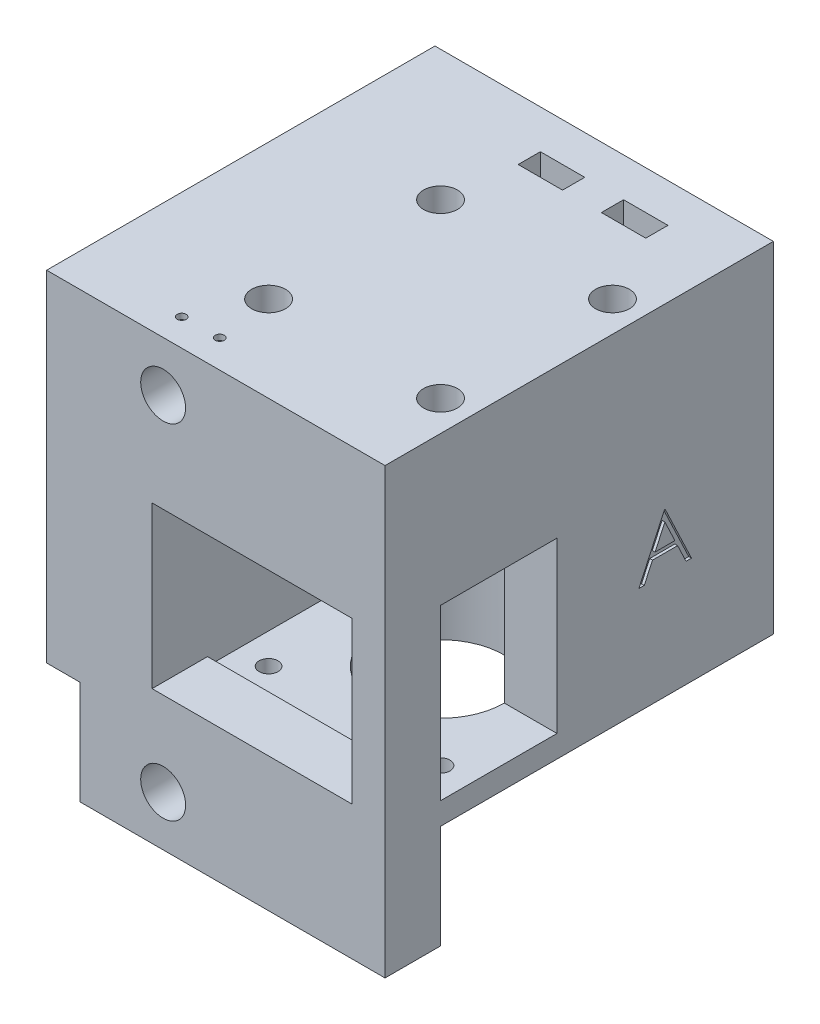
SolidWorks part; units mm, degrees
ref_plane "Front Plane" through (0, 0, 0) normal (0, 0, 1) x (1, 0, 0)
ref_plane "Top Plane" through (0, 0, 0) normal (0, 1, 0) x (1, 0, 0)
ref_plane "Right Plane" through (0, 0, 0) normal (1, 0, 0) x (0, 0, -1)
sketch "Sketch1" plane through (0, 0, 0) normal (0, 1, 0) x (1, 0, 0)
  line L0 (21, 42) -> (21, 33.028) construction
  line L1 (0, 0) -> (42, 0)
  line L2 (0, 0) -> (0, 42)
  line L3 (0, 42) -> (42, 42)
  line L4 (42, 0) -> (42, 42)
  line L5 (0, 21) -> (12.4001, 21) construction
  circle A0 centre (5.5, 36.5) radius 1.7
  circle A1 centre (36.5, 36.5) radius 1.7
  circle A2 centre (5.5, 5.5) radius 1.7
  circle A3 centre (36.5, 5.5) radius 1.7
  circle A4 centre (21, 21) radius 11.5
  dimension "D6" = 3.4
  dimension "D8" = 23
  dimension "D1" = 42
  dimension "D2" = 42
  dimension "D3" = 31
  dimension "D4" = 15.5
  dimension "D5" = 15.5
  dimension "D7" = 31
extrude "Boss-Extrude1" add sketch "Sketch1" along normal blind 4
sketch "Sketch2" plane through (0, 0, 0) normal (0, 0, 1) x (1, 0, 0)
  line L0 (-13, 61.325) -> (42, 61.325)
  line L2 (42, 61.325) -> (42, -18.675)
  line L3 (42, -18.675) -> (-13, -18.675)
  line L4 (-13, -18.675) -> (-13, 61.325)
  line L9 (47, -18.675) -> (12, -18.675) construction
  line L11 (14.5, 61.325) -> (14.5, 36.9623) construction
  line L12 (0, 4) -> (42, 4) construction
  line L13 (0, 5.5) -> (36, 5.5)
  line L14 (0, 5.5) -> (0, 34.5)
  line L15 (0, 34.5) -> (36, 34.5)
  line L16 (36, 5.5) -> (36, 34.5)
  line L17 (42, 4) -> (42, 0) construction
  line L18 (21, 4) -> (21, 28.3798) construction
  line L19 (0, 4) -> (0, 0) construction
  circle A0 centre (2, 52.325) radius 4.05
  circle A1 centre (2, -9.675) radius 4.05
  dimension "D3" = 8.1
  dimension "D1" = 55
  dimension "D2" = 80
  dimension "D4" = 9
  dimension "D5" = 9
  dimension "D7" = 6
  dimension "D8" = 1.5
  dimension "D9" = 29
  dimension "D10" = 19
extrude "Boss-Extrude2" add sketch "Sketch2" along normal blind 10
sketch "Sketch3" plane through (0, 0, 0) normal (0, 0, -1) x (-1, 0, 0)
  circle A0 centre (-2, -9.675) radius 4.05 construction
  circle A1 centre (-2, 52.325) radius 4.05 construction
  circle A2 centre (-2, -9.675) radius 4.05
  circle A3 centre (-2, 52.325) radius 4.05
sketch "Sketch4" plane through (0, 4, 0) normal (0, 1, 0) x (1, 0, 0)
  line L0 (0, 21) -> (9.5, 21)
  line L1 (0, 42) -> (0, 0) construction
  line L2 (32.5, 21) -> (42, 21)
  line L3 (42, 0) -> (42, 42) construction
  line L4 (0, 42) -> (42, 42)
  line L5 (42, 42) -> (42, 21)
  line L6 (0, 21) -> (0, 42)
  circle A0 centre (21, 21) radius 11.5 construction
  arc A1 (32.5, 21) -> (9.5, 21) centre (21, 21) ccw
extrude "Boss-Extrude4" add sketch "Sketch4" along normal up to surface (30.5 mm away) up to face at (18, 34.5, 5)
sketch "Sketch5" plane through (0, 0, 0) normal (0, 0, -1) x (-1, 0, 0)
  line L0 (0, 4) -> (0, 0) construction
  line L1 (-42, 34.5) -> (0, 34.5)
  line L2 (-42, 34.5) -> (-42, 61.325)
  line L3 (-42, 61.325) -> (0, 61.325)
  line L4 (0, 34.5) -> (0, 61.325)
  line L5 (-42, 61.325) -> (13, 61.325) construction
extrude "Boss-Extrude5" add sketch "Sketch5" along normal up to surface (42 mm away) up to face at (21, 17.25, -42)
sketch "Sketch6" plane through (0, 4, 0) normal (0, -1, 0) x (1, 0, 0)
  circle A0 centre (5.5, -36.5) radius 1.7 construction
  circle A1 centre (36.5, -36.5) radius 1.7 construction
  circle A2 centre (5.5, -36.5) radius 1.7
  circle A3 centre (36.5, -36.5) radius 1.7
extrude "Cut-Extrude1" cut sketch "Sketch6" against normal through all
sketch "Sketch7" plane through (0, 61.325, 0) normal (0, 1, 0) x (1, 0, 0)
  circle A0 centre (5.5, 36.5) radius 3.05
  circle A1 centre (36.5, 36.5) radius 3.05
  circle A2 centre (5.5, 5.5) radius 3.05
  circle A3 centre (36.5, 5.5) radius 3.05
  circle A4 centre (36.5, 5.5) radius 1.7 construction
  circle A5 centre (5.5, 5.5) radius 1.7 construction
  dimension "D1" = 6.1
extrude "Cut-Extrude2" cut sketch "Sketch7" against normal offset from surface (56.825 mm away) 4.5 up to face at (36.5, 0, -3.8)
extrude "Boss-Extrude7" add sketch "Sketch3" against normal blind 3
sketch "Sketch8" plane through (0, 61.325, 0) normal (0, 1, 0) x (1, 0, 0)
  circle A0 centre (0.4505, -5.1) radius 0.8
  circle A1 centre (7.1487, -4.9469) radius 0.8
  dimension "D1" = 1.6
extrude "Cut-Extrude3" cut sketch "Sketch8" against normal blind 1
ref_plane "Plane1" through (16.4, 0, 0) normal (1, 0, 0) x (0, 0, -1)
ref_plane "Plane2" through (0, 0, -10) normal (0, 0, 1) x (1, 0, 0)
sketch "Sketch9" plane through (0, 61.325, 0) normal (0, 1, 0) x (1, 0, 0)
  line L0 (-13, -10) -> (-19, -10)
  line L2 (-19, -10) -> (-19, 60)
  line L3 (-19, 60) -> (42, 60)
  line L4 (42, 60) -> (42, 42)
  line L5 (42, 42) -> (0, 42) construction
  line L6 (-13, -10) -> (-13, 0) construction
  line L7 (0, 0) -> (-13, 0) construction
  line L8 (0, 42) -> (0, 0) construction
  line L9 (-13, -10) -> (-13, 0)
  line L10 (0, 0) -> (-13, 0)
  line L11 (0, 42) -> (0, 0)
  line L12 (42, 42) -> (0, 42)
  dimension "D1" = 6
  dimension "D2" = 70
extrude "Boss-Extrude8" add sketch "Sketch9" against normal up to surface (61.325 mm away) up to face at (36.5, 0, -3.8)
sketch "Sketch10" plane through (0, 0, 0) normal (0, -1, 0) x (1, 0, 0)
  line L0 (42, -60) -> (-19, -60) construction
  circle A0 centre (-6.5, -52.5) radius 2
  circle A1 centre (-6.5, -37.5) radius 2
  dimension "D4" = 4
  dimension "D1" = 12.5
  dimension "D2" = 15
  dimension "D3" = 7.5
extrude "Cut-Extrude4" cut sketch "Sketch10" against normal blind 5
sketch "Sketch11" plane through (0, 0, -60) normal (0, 0, -1) x (-1, 0, 0)
  line L0 (-42, 61.325) -> (19, 61.325) construction
  circle A0 centre (-26, 53.325) radius 2.25
  circle A1 centre (-11, 53.325) radius 2.25
  dimension "D1" = 4.5
  dimension "D2" = 8
  dimension "D3" = 15
  dimension "D4" = 30
extrude "Cut-Extrude5" cut sketch "Sketch11" against normal blind 14
sketch "Sketch12" plane through (0, 61.325, 0) normal (0, 1, 0) x (1, 0, 0)
  line L0 (26, 60) -> (26, 46.8431) construction
  line L1 (7, 49) -> (15, 49)
  line L2 (7, 49) -> (7, 53)
  line L3 (7, 53) -> (15, 53)
  line L4 (15, 49) -> (15, 53)
  line L5 (22, 53) -> (30, 53)
  line L6 (22, 53) -> (22, 49)
  line L7 (22, 49) -> (30, 49)
  line L8 (30, 53) -> (30, 49)
  line L9 (42, 60) -> (-19, 60) construction
  line L12 (26, 46) -> (26, 60) construction
  line L13 (11, 60) -> (11, 46.8431) construction
  line L14 (11, 46) -> (11, 60) construction
  point P21 (11, 53)
  point P22 (26, 53)
  point P23 (15, 51)
  dimension "D1" = 7
  dimension "D2" = 4
  dimension "D3" = 8
extrude "Cut-Extrude6" cut sketch "Sketch12" against normal blind 13
sketch "Sketch13" plane through (42, 0, 0) normal (1, 0, 0) x (0, 0, -1)
  line L0 (21, 19.25) -> (60, 19.25) construction
  line L1 (21, 34.5) -> (21, 4) construction
  line L2 (60, 0) -> (60, 61.325) construction
  text T0 "A" font "Century Gothic" height 10
extrude "Cut-Extrude7" cut sketch "Sketch13" against normal blind 0.5
